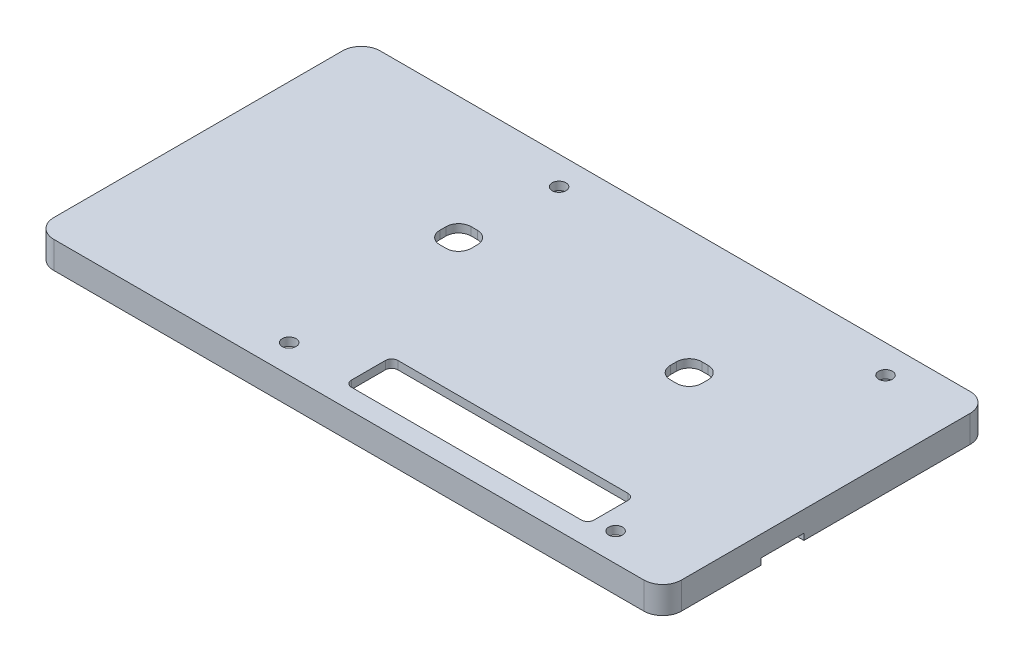
SolidWorks part; units mm, degrees
ref_plane "Front Plane" through (0, 0, 0) normal (0, 0, 1) x (1, 0, 0)
ref_plane "Top Plane" through (0, 0, 0) normal (0, 1, 0) x (1, 0, 0)
ref_plane "Right Plane" through (0, 0, 0) normal (1, 0, 0) x (0, 0, -1)
other "Configuration Table"
sketch "草图1" plane through (0, 0, 0) normal (0, 1, 0) x (1, 0, 0)
  line L1 (-48.8285, 31.982) -> (51.1715, 31.982)
  line L2 (-48.8285, 31.982) -> (-48.8285, -20.018)
  line L3 (-48.8285, -20.018) -> (51.1715, -20.018)
  line L4 (51.1715, 31.982) -> (51.1715, -20.018)
  dimension "D1" = 100
  dimension "D2" = 52
extrude "凸台-拉伸1" add sketch "草图1" along normal blind 8.6
sketch "草图2" plane through (0, 0, 0) normal (0, -1, 0) x (1, 0, 0)
  line L0 (51.1715, -31.982) -> (-48.8285, -31.982) construction
  line L1 (49.6715, -30.482) -> (-47.3285, -30.482)
  line L2 (49.6715, -30.482) -> (49.6715, 18.518)
  line L3 (49.6715, 18.518) -> (-47.3285, 18.518)
  line L4 (-47.3285, -30.482) -> (-47.3285, 18.518)
  line L5 (-48.8285, -31.982) -> (-48.8285, 20.018) construction
  line L6 (-48.8285, 20.018) -> (51.1715, 20.018) construction
  line L7 (51.1715, 20.018) -> (51.1715, -31.982) construction
  dimension "D1" = 1.5
  dimension "D2" = 1.5
  dimension "D3" = 1.5
  dimension "D4" = 1.5
extrude "切除-拉伸1" cut sketch "草图2" against normal blind 3
sketch "草图3" plane through (0, 3, 0) normal (0, -1, 0) x (1, 0, 0)
  line L0 (51.1715, -31.982) -> (-48.8285, -31.982) construction
  line L1 (35.9314, 9.319) -> (-2.7006, 9.319)
  line L2 (35.9314, 9.319) -> (35.9314, 16.7184)
  line L3 (35.9314, 16.7184) -> (-2.7006, 16.7184)
  line L4 (-2.7006, 9.319) -> (-2.7006, 16.7184)
  line L5 (-16.3285, -9.982) -> (-11.3285, -9.982)
  line L6 (-16.3285, -9.982) -> (-16.3285, -14.982)
  line L7 (-16.3285, -14.982) -> (-11.3285, -14.982)
  line L8 (-11.3285, -9.982) -> (-11.3285, -14.982)
  line L9 (-48.8285, -31.982) -> (-48.8285, 20.018) construction
  line L10 (48.159, -31.7129) -> (-45.8412, -31.7129) construction
  line L11 (20.6715, -9.7129) -> (25.6715, -9.7129)
  line L12 (20.6715, -9.7129) -> (20.6715, -14.7129)
  line L13 (20.6715, -14.7129) -> (25.6715, -14.7129)
  line L14 (25.6715, -9.7129) -> (25.6715, -14.7129)
  line L15 (51.1715, 20.018) -> (51.1715, -31.982) construction
  line L16 (-48.8285, 20.018) -> (51.1715, 20.018) construction
  circle A0 centre (-12.8285, 15.518) radius 1.1
  circle A1 centre (39.1715, 15.518) radius 1.1
  circle A2 centre (39.1715, -27.482) radius 1.1
  circle A3 centre (-12.8285, -27.482) radius 1.1
  dimension "D9" = 4.5
  dimension "D1" = 5
  dimension "D2" = 5
  dimension "D3" = 17
  dimension "D4" = 32.5
  dimension "D5" = 5
  dimension "D6" = 5
  dimension "D7" = 17
  dimension "D8" = 25.5
  dimension "D10" = 36
  dimension "D11" = 4.5
  dimension "D12" = 12
  dimension "D13" = 12
  dimension "D14" = 4.5
  dimension "D15" = 4.5
  dimension "D16" = 36
extrude "切除-拉伸2" cut sketch "草图3" against normal through all
sketch "草图8" plane through (0, 3, 0) normal (0, -1, 0) x (1, 0, 0)
  circle A0 centre (39.1715, -27.482) radius 2
  circle A1 centre (-12.8285, -27.482) radius 2
  circle A2 centre (-12.8285, 15.518) radius 2
  circle A3 centre (39.1715, 15.518) radius 2
fillet "圆角1" radius 2 8 edges at (25.6715, 5.8, -14.7129) (25.6715, 5.8, -9.7129) (20.6715, 5.8, -9.7129) (20.6715, 5.8, -14.7129) (-16.3285, 5.8, -14.982) (-11.3285, 5.8, -14.982) (-11.3285, 5.8, -9.982) (-16.3285, 5.8, -9.982)
sketch "草图4" plane through (0, 0, 0) normal (0, -1, 0) x (1, 0, 0)
  line L0 (51.1715, 20.018) -> (51.1715, -31.982) construction
  line L1 (51.1715, -2.482) -> (49.6715, -2.482)
  line L2 (51.1715, -2.482) -> (51.1715, 4.318)
  line L3 (51.1715, 4.318) -> (49.6715, 4.318)
  line L4 (49.6715, -2.482) -> (49.6715, 4.318)
  line L5 (49.6715, -30.482) -> (49.6715, 18.518) construction
  line L6 (51.1715, -31.982) -> (-48.8285, -31.982) construction
  dimension "D1" = 29.5
  dimension "D2" = 36.3
extrude "切除-拉伸3" cut sketch "草图4" against normal blind 1
sketch "草图5" plane through (0, 8.6, 0) normal (0, 1, 0) x (1, 0, 0)
  line L0 (51.1715, -20.018) -> (51.1715, 31.982) construction
  line L1 (-47.3285, 30.482) -> (49.6715, 30.482)
  line L2 (-47.3285, 30.482) -> (-47.3285, -18.518)
  line L3 (-47.3285, -18.518) -> (49.6715, -18.518)
  line L4 (49.6715, 30.482) -> (49.6715, -18.518)
  line L5 (-48.8285, -20.018) -> (51.1715, -20.018) construction
  line L6 (-48.8285, 31.982) -> (-48.8285, -20.018) construction
  line L7 (51.1715, 31.982) -> (-48.8285, 31.982) construction
  dimension "D1" = 1.5
  dimension "D2" = 1.5
  dimension "D3" = 1.5
  dimension "D4" = 1.5
extrude "切除-拉伸4" cut sketch "草图5" against normal blind 3
sketch "草图7" plane through (0, 5.6, 0) normal (0, 1, 0) x (1, 0, 0)
  line L0 (-8.6885, -18.518) -> (-8.6885, 4.782)
  line L1 (-47.3285, -18.518) -> (49.6715, -18.518) construction
  line L2 (-8.6885, 4.782) -> (-27.6285, 4.782)
  line L3 (-27.6285, 4.782) -> (-27.6285, 30.482)
  line L4 (49.6715, 30.482) -> (-47.3285, 30.482) construction
  line L5 (-27.6285, 30.482) -> (-26.1285, 30.482)
  line L6 (-26.1285, 30.482) -> (-26.1285, 6.282)
  line L7 (-26.1285, 6.282) -> (-8.6885, 6.282)
  line L8 (-8.6885, 6.282) -> (-8.6885, 30.482)
  line L9 (-8.6885, 30.482) -> (-7.1885, 30.482)
  line L10 (-7.1885, 30.482) -> (-7.1885, -4.518)
  line L11 (-7.1885, -4.518) -> (49.6715, -4.518)
  line L12 (49.6715, -18.518) -> (49.6715, 30.482) construction
  line L13 (49.6715, -4.518) -> (49.6715, -6.018)
  line L14 (49.6715, -6.018) -> (-7.1885, -6.018)
  line L15 (-7.1885, -6.018) -> (-7.1885, -18.518)
  line L16 (-7.1885, -18.518) -> (-8.6885, -18.518)
  line L17 (-48.8285, -20.018) -> (51.1715, -20.018) construction
  line L18 (51.1715, -20.018) -> (51.1715, 31.982) construction
  line L19 (51.1715, 31.982) -> (-48.8285, 31.982) construction
  line L20 (16.9715, 30.482) -> (16.9715, 6.682)
  line L21 (16.9715, 6.682) -> (30.1715, 6.682)
  line L22 (30.1715, 6.682) -> (30.1715, 30.482)
  line L23 (30.1715, 30.482) -> (28.6715, 30.482)
  line L24 (28.6715, 30.482) -> (28.6715, 8.182)
  line L25 (28.6715, 8.182) -> (18.4715, 8.182)
  line L26 (18.4715, 8.182) -> (18.4715, 30.482)
  line L27 (18.4715, 30.482) -> (16.9715, 30.482)
  dimension "D1" = 14
  dimension "D2" = 1.5
  dimension "D3" = 58.36
  dimension "D4" = 1.5
  dimension "D5" = 78.8
  dimension "D6" = 27.2
  dimension "D7" = 1.5
  dimension "D8" = 1.5
  dimension "D9" = 21
  dimension "D10" = 25.3
  dimension "D11" = 34.2
  dimension "D12" = 1.5
  dimension "D13" = 1.5
  dimension "D14" = 1.5
extrude "凸台-拉伸2" add sketch "草图7" along normal through all
fillet "圆角2" radius 3 4 edges at (51.1715, 4.3, 20.018) (51.1715, 4.3, -31.982) (-48.8285, 4.3, -31.982) (-48.8285, 4.3, 20.018)
fillet "圆角3" radius 2 30 edges at (-47.3285, 7.1, 18.518) (-47.3285, 7.1, -30.482) (49.6715, 7.1, -30.482) (49.6715, 7.1, 18.518) (49.6715, 1.5, -30.482) (49.6715, 1.5, 18.518) (-47.3285, 1.5, 18.518) (-47.3285, 1.5, -30.482) (-27.6285, 7.1, -4.782) (-27.6285, 7.1, -30.482) (-26.1285, 7.1, -30.482) (-26.1285, 7.1, -6.282) (-8.6885, 7.1, 18.518) (-8.6885, 7.1, -4.782) (-8.6885, 7.1, -6.282) (-8.6885, 7.1, -30.482) (-7.1885, 7.1, -30.482) (18.4715, 7.1, -8.182) (28.6715, 7.1, -8.182) (18.4715, 7.1, -30.482) (28.6715, 7.1, -30.482) (16.9715, 7.1, -30.482) (16.9715, 7.1, -6.682) (30.1715, 7.1, -6.682) (30.1715, 7.1, -30.482) (49.6715, 7.1, 4.518) (-7.1885, 7.1, 4.518) (-7.1885, 7.1, 6.018) (-7.1885, 7.1, 18.518) (49.6715, 7.1, 6.018)
fillet "圆角5" radius 1 4 edges at (35.9314, 4.3, 16.7184) (35.9314, 4.3, 9.319) (-2.7006, 4.3, 9.319) (-2.7006, 4.3, 16.7184)
sketch "草图9" plane through (51.1715, 0, 0) normal (1, 0, 0) x (0, 0, -1)
  line L0 (31.982, 8.6) -> (31.982, 0) construction
  line L1 (-20.018, 8.6) -> (31.982, 8.6)
  line L2 (-20.018, 8.6) -> (-20.018, 4.3)
  line L3 (-20.018, 4.3) -> (31.982, 4.3)
  line L4 (31.982, 8.6) -> (31.982, 4.3)
extrude "切除-拉伸5" cut sketch "草图9" against normal through all
